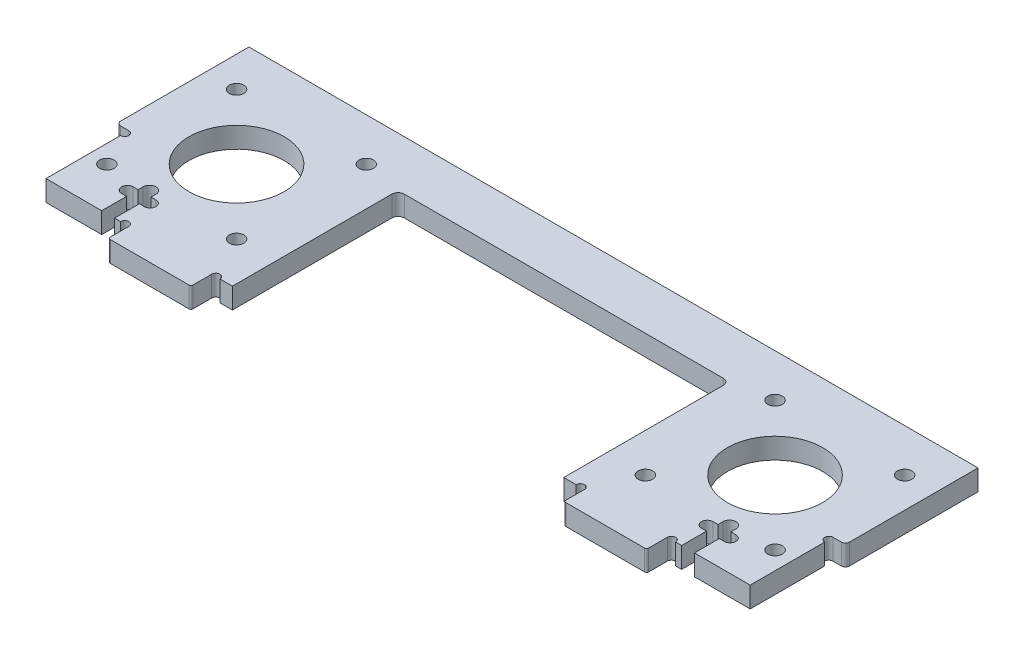
SolidWorks part; units mm, degrees
ref_plane "정면" through (0, 0, 0) normal (0, 0, 1) x (1, 0, 0)
ref_plane "윗면" through (0, 0, 0) normal (0, 1, 0) x (1, 0, 0)
ref_plane "우측면" through (0, 0, 0) normal (1, 0, 0) x (0, 0, -1)
sketch "스케치1" plane through (0, 0, 0) normal (0, 1, 0) x (1, 0, 0)
  line L1 (0, 0) -> (170, 0)
  line L2 (0, 0) -> (0, 52)
  line L3 (0, 52) -> (170, 52)
  line L4 (170, 0) -> (170, 52)
  dimension "D1" = 170
  dimension "D2" = 52
extrude "보스-돌출1" add sketch "스케치1" along normal blind 5
sketch "스케치2" plane through (0, 5, 0) normal (0, 1, 0) x (1, 0, 0)
  line L0 (85, 52) -> (85, 0) construction
  line L1 (170, 52) -> (0, 52) construction
  line L2 (0, 0) -> (170, 0) construction
  line L3 (150, 26) -> (20, 26) construction
  line L4 (134.35, 10.35) -> (165.65, 10.35) construction
  line L5 (134.35, 10.35) -> (134.35, 41.65) construction
  line L6 (134.35, 41.65) -> (165.65, 41.65) construction
  line L7 (165.65, 10.35) -> (165.65, 41.65) construction
  line L8 (134.35, 10.35) -> (165.65, 41.65) construction
  line L9 (134.35, 41.65) -> (165.65, 10.35) construction
  line L10 (170, 0) -> (170, 52) construction
  line L11 (35.65, 41.65) -> (4.35, 10.35) construction
  line L12 (35.65, 10.35) -> (4.35, 41.65) construction
  line L13 (4.35, 10.35) -> (4.35, 41.65) construction
  line L14 (35.65, 41.65) -> (4.35, 41.65) construction
  line L15 (35.65, 10.35) -> (35.65, 41.65) construction
  line L16 (35.65, 10.35) -> (4.35, 10.35) construction
  circle A0 centre (150, 26) radius 11.5
  circle A1 centre (165.65, 41.65) radius 1.75
  circle A2 centre (134.35, 41.65) radius 1.75
  circle A3 centre (165.65, 10.35) radius 1.75
  circle A4 centre (134.35, 10.35) radius 1.75
  circle A5 centre (35.65, 10.35) radius 1.75
  circle A6 centre (4.35, 10.35) radius 1.75
  circle A7 centre (35.65, 41.65) radius 1.75
  circle A8 centre (4.35, 41.65) radius 1.75
  circle A9 centre (20, 26) radius 11.5
  point P16 (170, 26)
  point P25 (85, 26)
  dimension "D1" = 23
  dimension "D3" = 3.5
  dimension "D2" = 31.3
  dimension "D4" = 20
extrude "컷-돌출1" cut sketch "스케치2" against normal blind 5
sketch "스케치3" plane through (0, 5, 0) normal (0, 1, 0) x (1, 0, 0)
  line L1 (0, 0) -> (170, 0) construction
  line L2 (130, 0) -> (150, 0)
  line L3 (130, 0) -> (130, -5)
  line L4 (130, -5) -> (150, -5)
  line L5 (150, 0) -> (150, -5)
  line L6 (130, -5) -> (40, -5) construction
  line L7 (20, 0) -> (40, 0)
  line L8 (20, 0) -> (20, -5)
  line L9 (20, -5) -> (40, -5)
  line L10 (40, 0) -> (40, -5)
  line L11 (150, -5) -> (170, -5) construction
  line L12 (170, -5) -> (170, 0) construction
  line L13 (0, 0) -> (0, -5) construction
  line L14 (0, -5) -> (20, -5) construction
  dimension "D1" = 20
  dimension "D2" = 20
  dimension "D3" = 5
extrude "보스-돌출2" add sketch "스케치3" against normal blind 5
sketch "스케치4" plane through (0, 5, 0) normal (0, 1, 0) x (1, 0, 0)
  line L0 (40, 0) -> (130, 0) construction
  line L1 (150, 0) -> (170, 0) construction
  line L2 (0, 0) -> (20, 0) construction
  circle A0 centre (129, 0) radius 1
  circle A1 centre (151, 0) radius 1
  circle A2 centre (19, 0) radius 1
  circle A3 centre (41, 0) radius 1
  dimension "D1" = 2
extrude "컷-돌출2" cut sketch "스케치4" against normal blind 5
sketch "스케치5" plane through (0, 5, 0) normal (0, 1, 0) x (1, 0, 0)
  line L0 (156.55, 0) -> (156.55, 6)
  line L1 (153.45, 10) -> (156.55, 10) construction
  line L2 (152.25, 6) -> (152.25, 8.8) construction
  line L3 (156.55, 6) -> (156.55, 8.8) construction
  line L4 (153.45, 0) -> (156.55, 0)
  line L5 (152.25, 8.8) -> (153.45, 8.8)
  line L6 (153.45, 0) -> (153.45, 6)
  line L7 (157.75, 8.8) -> (157.75, 6) construction
  line L8 (153.45, 6) -> (152.25, 6)
  line L9 (153.45, 8.8) -> (153.45, 6) construction
  line L10 (156.55, 8.8) -> (156.55, 10)
  line L11 (153.45, 6) -> (156.55, 6) construction
  line L12 (153.45, 8.8) -> (156.55, 8.8) construction
  line L13 (156.55, 8.8) -> (157.75, 8.8)
  line L14 (153.45, 8.8) -> (153.45, 10)
  line L15 (155, 10) -> (155, 12.1831) construction
  line L16 (157.75, 6) -> (156.55, 6)
  line L34 (170, 0) -> (170, 52) construction
  line L35 (85, 52) -> (85, 0) construction
  line L36 (170, 52) -> (0, 52) construction
  line L37 (42, 0) -> (128, 0) construction
  line L46 (15, 10) -> (15, 12.1831) construction
  line L47 (16.55, 8.8) -> (13.45, 8.8) construction
  line L48 (16.55, 6) -> (13.45, 6) construction
  line L49 (16.55, 8.8) -> (16.55, 6) construction
  line L50 (12.25, 8.8) -> (12.25, 6) construction
  line L51 (13.45, 6) -> (13.45, 8.8) construction
  line L52 (17.75, 6) -> (17.75, 8.8) construction
  line L53 (16.55, 10) -> (13.45, 10) construction
  line L63 (12.25, 6) -> (13.45, 6)
  line L64 (16.55, 8.8) -> (16.55, 10)
  line L65 (13.45, 8.8) -> (12.25, 8.8)
  line L66 (13.45, 8.8) -> (13.45, 10)
  line L67 (16.55, 6) -> (17.75, 6)
  line L68 (16.55, 0) -> (16.55, 6)
  line L69 (17.75, 8.8) -> (16.55, 8.8)
  line L70 (16.55, 0) -> (13.45, 0)
  line L71 (13.45, 0) -> (13.45, 6)
  arc A0 (156.55, 10) -> (153.45, 10) centre (155, 10) ccw
  arc A1 (152.25, 8.8) -> (152.25, 6) centre (152.25, 7.4) ccw
  arc A2 (157.75, 6) -> (157.75, 8.8) centre (157.75, 7.4) ccw
  arc A9 (12.25, 6) -> (12.25, 8.8) centre (12.25, 7.4) cw
  arc A10 (17.75, 8.8) -> (17.75, 6) centre (17.75, 7.4) cw
  arc A11 (13.45, 10) -> (16.55, 10) centre (15, 10) cw
  dimension "D1" = 3.1
  dimension "D2" = 10
  dimension "D3" = 5.5
  dimension "D4" = 2.8
  dimension "D12" = 15
extrude "컷-돌출3" cut sketch "스케치5" against normal blind 10
fillet "필렛1" radius 0.5 4 edges at (20, 2.5, 5) (130, 2.5, 5) (150, 2.5, 5) (40, 2.5, 5)
sketch "스케치6" plane through (0, 5, 0) normal (0, 1, 0) x (1, 0, 0)
  line L0 (85, 52) -> (85, 0) construction
  line L1 (170, 52) -> (0, 52) construction
  line L3 (85, 21) -> (85, 31) construction
  line L4 (81, 21) -> (81, 31)
  line L5 (89, 21) -> (89, 31)
  arc A0 (81, 21) -> (89, 21) centre (85, 21) ccw
  arc A1 (89, 31) -> (81, 31) centre (85, 31) ccw
  point P8 (85, 26)
  dimension "D1" = 4
  dimension "D2" = 10
extrude "컷-돌출4" [suppressed] cut sketch "스케치6" against normal blind 10
sketch "스케치7" plane through (0, 5, 0) normal (0, 1, 0) x (1, 0, 0)
  line L0 (170, 0) -> (170, 52) construction
  line L1 (170, 52) -> (173, 52)
  line L2 (170, 52) -> (170, 20)
  line L3 (170, 20) -> (173, 20)
  line L4 (173, 52) -> (173, 20)
  line L5 (0, 52) -> (0, 0) construction
  line L6 (0, 52) -> (-3, 52)
  line L7 (0, 52) -> (0, 20)
  line L8 (0, 20) -> (-3, 20)
  line L9 (-3, 52) -> (-3, 20)
  line L10 (156.55, 0) -> (170, 0) construction
  dimension "D1" = 3
  dimension "D2" = 20
  dimension "D3" = 32
extrude "보스-돌출3" add sketch "스케치7" against normal blind 5
sketch "스케치8" plane through (0, 5, 0) normal (0, 1, 0) x (1, 0, 0)
  line L0 (170, 0) -> (170, 20) construction
  line L2 (0, 20) -> (0, 0) construction
  circle A0 centre (170, 19) radius 1
  circle A2 centre (0, 19) radius 1
extrude "컷-돌출5" cut sketch "스케치8" against normal blind 5
sketch "스케치9" plane through (0, 5, 0) normal (0, 1, 0) x (1, 0, 0)
  line L0 (85, 52) -> (85, 0) construction
  line L1 (173, 52) -> (-3, 52) construction
  line L2 (42, 0) -> (128, 0) construction
  line L4 (45, 40) -> (125, 40)
  line L5 (45, 40) -> (45, 0)
  line L6 (45, 0) -> (125, 0)
  line L7 (125, 40) -> (125, 0)
  line L8 (45, 40) -> (125, 0) construction
  line L9 (45, 0) -> (125, 40) construction
  point P6 (85, 20)
  dimension "D1" = 40
  dimension "D2" = 80
extrude "컷-돌출6" cut sketch "스케치9" against normal blind 10
fillet "필렛2" radius 1.5 2 edges at (125, 2.5, -40) (45, 2.5, -40)
fillet "필렛3" radius 1 2 edges at (173, 2.5, -20) (-3, 2.5, -20)
